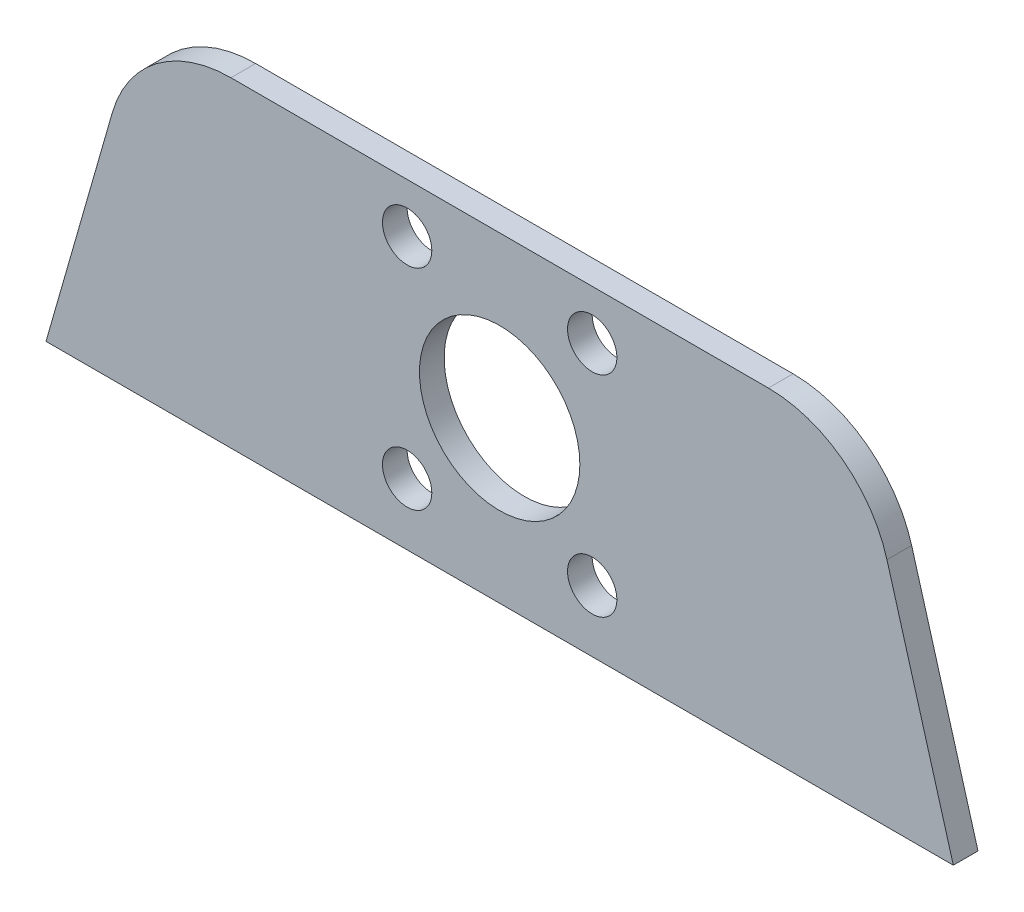
SolidWorks part; units mm, degrees
material "Thornel Mat VMA"
ref_plane "前视基准面" through (0, 0, 0) normal (0, 0, 1) x (1, 0, 0)
ref_plane "上视基准面" through (0, 0, 0) normal (0, 1, 0) x (1, 0, 0)
ref_plane "右视基准面" through (0, 0, 0) normal (1, 0, 0) x (0, 0, -1)
sketch "草图1" plane through (0, 0, 0) normal (0, 0, 1) x (1, 0, 0)
  line L0 (-42.5, 45) -> (57.5, 45) construction
  line L1 (0, 0) -> (15, 0) construction
  line L2 (0, 0) -> (0, 17) construction
  line L3 (0, 17) -> (15, 17) construction
  line L4 (15, 0) -> (15, 17) construction
  line L9 (7.5, 21) -> (7.5, -5) construction
  line L10 (-29.2693, -5) -> (44.2693, -5)
  line L12 (-21.814, 21) -> (36.814, 21)
  line L14 (-21.814, 21) -> (-29.2693, -5)
  line L15 (36.814, 21) -> (44.2693, -5)
  circle A0 centre (15, 17) radius 2
  circle A1 centre (15, 0) radius 2
  circle A2 centre (0, 0) radius 2
  circle A3 centre (0, 17) radius 2
  circle A4 centre (-42.5, 45) radius 26.5 construction
  circle A5 centre (57.5, 45) radius 26.5 construction
  circle A6 centre (7.5, 8) radius 6.5
  point P23 (7.5, 17)
  dimension "D3" = 4
  dimension "D4" = 53
  dimension "D10" = 13
  dimension "D1" = 17
  dimension "D2" = 15
  dimension "D5" = 106
  dimension "D6" = 50
  dimension "D7" = 5
  dimension "D8" = 4
  dimension "D9" = 24
extrude "凸台-拉伸1" add sketch "草图1" along normal blind 2
fillet "圆角1" radius 10 2 edges at (36.814, 21, 1) (-21.814, 21, 1)
